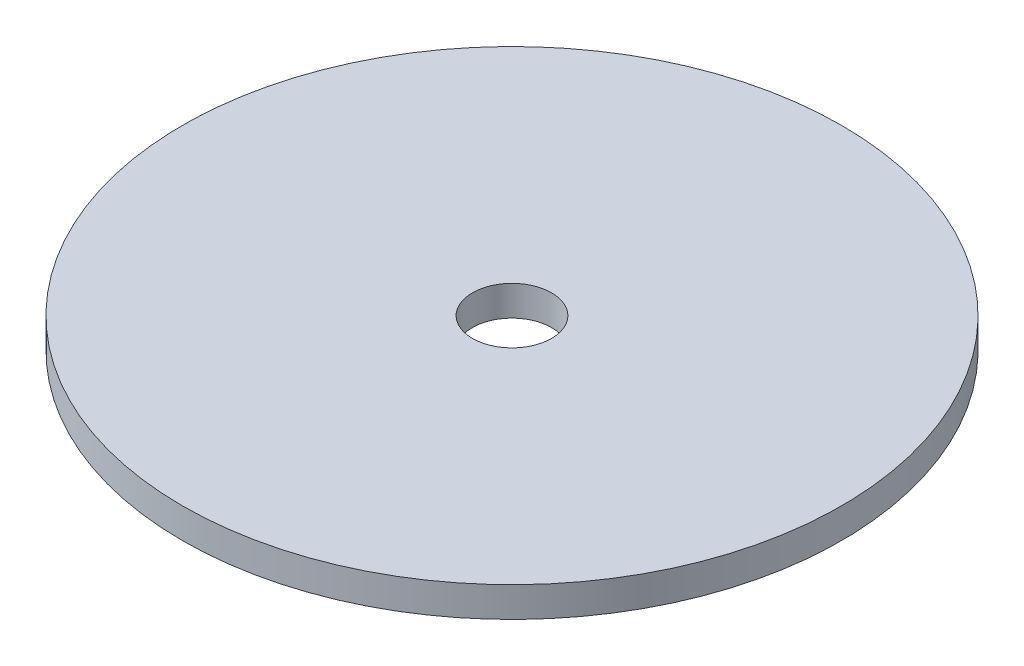
SolidWorks part; units mm, degrees
ref_plane "正面" through (0, 0, 0) normal (0, 0, 1) x (1, 0, 0)
ref_plane "平面" through (0, 0, 0) normal (0, 1, 0) x (1, 0, 0)
ref_plane "右側面" through (0, 0, 0) normal (1, 0, 0) x (0, 0, -1)
sketch "ｽｹｯﾁ2" plane through (0, 0, 0) normal (0, 1, 0) x (-1, 0, 0)
  circle A0 centre (0, 0) radius 17.5
  circle A2 centre (0, 0) radius 2.1
  dimension "D1" = 35
  dimension "D2" = 4.2
extrude "ﾎﾞｽ - 押し出し2" add sketch "ｽｹｯﾁ2" along normal blind 1.6
